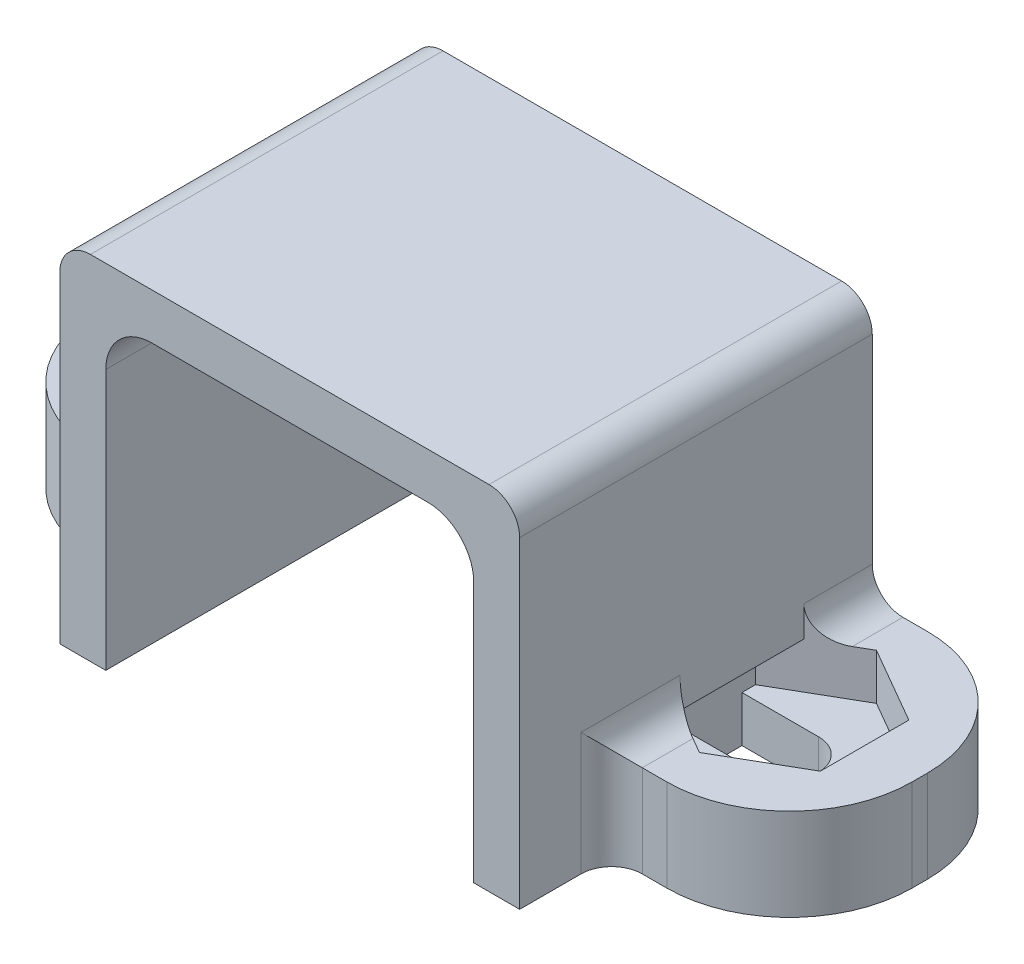
SolidWorks part; units mm, degrees
ref_plane "Front Plane" through (0, 0, 0) normal (0, 0, 1) x (1, 0, 0)
ref_plane "Top Plane" through (0, 0, 0) normal (0, 1, 0) x (1, 0, 0)
ref_plane "Right Plane" through (0, 0, 0) normal (1, 0, 0) x (0, 0, -1)
sketch "Sketch1" plane through (0, 0, 0) normal (0, 0, 1) x (1, 0, 0)
  line L0 (0, 0) -> (1.5, 0)
  line L1 (1.5, 0) -> (1.5, 10)
  line L2 (0, 0) -> (0, 10)
  line L3 (0, 10) -> (0, 11.5)
  line L4 (0, 11.5) -> (15, 11.5)
  line L5 (15, 11.5) -> (15, 0)
  line L6 (15, 0) -> (13.5, 0)
  line L7 (13.5, 0) -> (13.5, 10)
  line L8 (13.5, 10) -> (1.5, 10)
extrude "Boss-Extrude1" add sketch "Sketch1" along normal blind 17
sketch "Sketch12" plane through (0, 0, 0) normal (0, -1, 0) x (1, 0, 0)
  line L2 (15, 8) -> (0, 8)
  line L3 (15, 17) -> (15, 0) construction
  line L4 (0, 17) -> (0, 0) construction
split "Split2" trim tools "Sketch12" bodies to split 101 resulting bodies 116 117
combine bodies "Combine2" operation type add bodies to combine 116 117
sketch "Sketch13" plane through (0, 0, 0) normal (0, -1, 0) x (1, 0, 0)
  line L0 (7.5, 0) -> (7.5, 1.8013) construction
  line L1 (0, 0) -> (-5.8, 0)
  line L2 (0, 0) -> (0, 8.5)
  line L3 (0, 8.5) -> (-5.8, 8.5)
  line L4 (-5.8, 0) -> (-5.8, 8.5)
  line L5 (1.5, 0) -> (13.5, 0) construction
  line L6 (20.8, 0) -> (20.8, 8.5)
  line L7 (15, 8.5) -> (20.8, 8.5)
  line L8 (15, 0) -> (15, 8.5)
  line L9 (15, 0) -> (20.8, 0)
extrude "Boss-Extrude10" add sketch "Sketch13" against normal blind 3
fillet "Fillet7" radius 4 4 edges at (20.8, 1.5, 8.5) (20.8, 1.5, 0) (-5.8, 1.5, 0) (-5.8, 1.5, 8.5)
sketch "Sketch15" plane through (0, 0, 0) normal (-1, 0, 0) x (0, 0, 1)
  line L0 (0, 3) -> (17, 3)
  line L1 (17, 11.5) -> (17, 0) construction
split "Split3" trim tools "Sketch15" bodies to split 120 resulting bodies 121 122 123
sketch "Sketch16" plane through (0, 3, 0) normal (0, 1, 0) x (1, 0, 0)
  line L0 (1, -4.25) -> (-1.5, -4.25) construction
  line L2 (13.5, 0) -> (1.5, 0) construction
  line L3 (-1.5, -7.1368) -> (1, -5.6934)
  line L4 (1, -5.6934) -> (1, -2.8066)
  line L5 (1, -2.8066) -> (-1.5, -1.3632)
  line L6 (-1.5, -1.3632) -> (-4, -2.8066)
  line L7 (-4, -2.8066) -> (-4, -5.6934)
  line L8 (-4, -5.6934) -> (-1.5, -7.1368)
  line L9 (7.5, 0) -> (7.5, -2.8066) construction
  line L10 (7.5, -2.8066) -> (7.5, -4.25) construction
  line L11 (7.5, -4.25) -> (-1.5, -4.25) construction
  line L12 (-4, -2.8066) -> (-1.5, -1.3632)
  line L13 (-1.5, -7.1368) -> (-4, -5.6934)
  line L14 (1, -5.6934) -> (-1.5, -7.1368)
  line L15 (-1.5, -1.3632) -> (1, -2.8066)
  line L16 (14, -4.25) -> (16.5, -4.25) construction
  line L17 (16.5, -1.3632) -> (14, -2.8066)
  line L18 (14, -5.6934) -> (16.5, -7.1368)
  line L19 (16.5, -7.1368) -> (19, -5.6934)
  line L20 (19, -2.8066) -> (16.5, -1.3632)
  line L21 (19, -5.6934) -> (16.5, -7.1368)
  line L22 (19, -2.8066) -> (19, -5.6934)
  line L23 (16.5, -1.3632) -> (19, -2.8066)
  line L24 (14, -2.8066) -> (16.5, -1.3632)
  line L25 (14, -5.6934) -> (14, -2.8066)
  line L26 (16.5, -7.1368) -> (14, -5.6934)
extrude "Cut-Extrude1" cut sketch "Sketch16" against normal blind 1.5 contours L7 L8 L3 L4 L5 L6 | L25 L18 L19 L22 L20 L17
sketch "Sketch17" plane through (0, 1.5, 0) normal (0, 1, 0) x (1, 0, 0)
  line L0 (-1.5, -1.3632) -> (-1.5, -7.1368) construction
  line L3 (7.5, 0) -> (7.5, -1.3632) construction
  line L5 (16.5, -1.3632) -> (16.5, -7.1368) construction
  line L6 (16.5, -5.25) -> (14, -5.25)
  line L8 (16.5, -3.25) -> (14, -3.25)
  line L9 (14, -3.25) -> (14, -5.25)
  line L10 (1, -3.25) -> (1, -5.25)
  line L11 (-1.5, -3.25) -> (1, -3.25)
  line L12 (-1.5, -5.25) -> (1, -5.25)
  arc A0 (-1.5, -3.25) -> (-1.5, -5.25) centre (-1.5, -4.25) ccw
  arc A1 (16.5, -3.25) -> (16.5, -5.25) centre (16.5, -4.25) cw
extrude "Cut-Extrude2" cut sketch "Sketch17" against normal through all
combine bodies "Combine3" operation type add bodies to combine 123 128 127
fillet "Скругление1" radius 1 4 edges at (0, 3, 7.3854) (15, 3, 7.3854)
fillet "Скругление2" radius 1 4 edges at (0, 11.5, 8.5) (15, 11.5, 8.5)
fillet "Скругление3" radius 1.5 2 edges at (1.5, 10, 8.5) (13.5, 10, 8.5)
sketch "Эскиз1" plane through (0, 0, 0) normal (0, 0, 1) x (1, 0, 0)
  line L1 (-48.71, 32.1329) -> (27.0648, 32.1329)
  line L2 (-48.71, 32.1329) -> (-48.71, -4.2865)
  line L3 (-48.71, -4.2865) -> (27.0648, -4.2865)
  line L4 (27.0648, 32.1329) -> (27.0648, -4.2865)
  line L5 (-48.71, 32.1329) -> (27.0648, -4.2865) construction
  line L6 (-48.71, -4.2865) -> (27.0648, 32.1329) construction
  point P0 (-10.8226, 13.9232)
extrude "Вырез-Вытянуть1" cut sketch "Эскиз1" along normal blind 10 from offset 11.5
